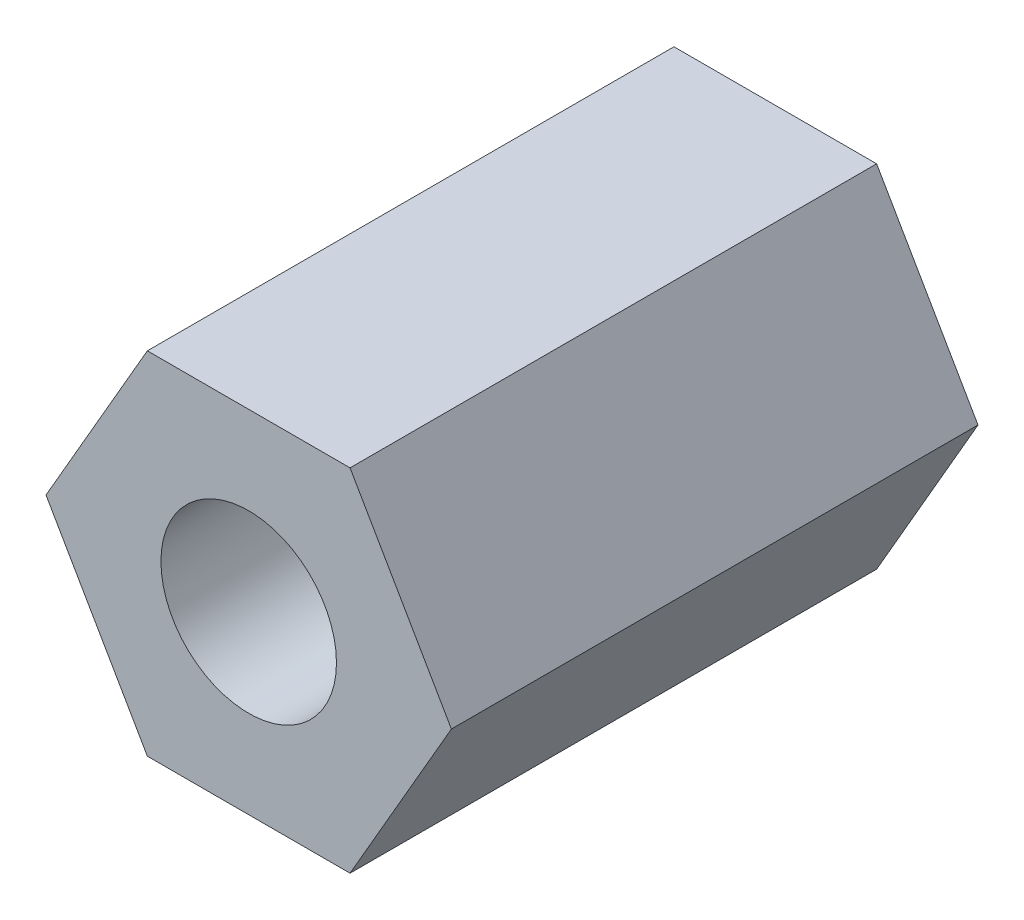
SolidWorks part; units mm, degrees
ref_plane "Front Plane" through (0, 0, 0) normal (0, 0, 1) x (1, 0, 0)
ref_plane "Top Plane" through (0, 0, 0) normal (0, 1, 0) x (1, 0, 0)
ref_plane "Right Plane" through (0, 0, 0) normal (1, 0, 0) x (0, 0, -1)
sketch "Sketch1" plane through (0, 0, 0) normal (0, 0, 1) x (1, 0, 0)
  line L1 (3.4641, 0) -> (1.7321, 3)
  line L2 (1.7321, 3) -> (-1.7321, 3)
  line L3 (-1.7321, 3) -> (-3.4641, 0)
  line L4 (-3.4641, 0) -> (-1.7321, -3)
  line L5 (-1.7321, -3) -> (1.7321, -3)
  line L6 (1.7321, -3) -> (3.4641, 0)
  circle A0 centre (0, 0) radius 1.5
  circle A2 centre (0, 0) radius 3 construction
  dimension "D1" = 3
  dimension "D2" = 6
extrude "Boss-Extrude1" add sketch "Sketch1" along normal blind 9
